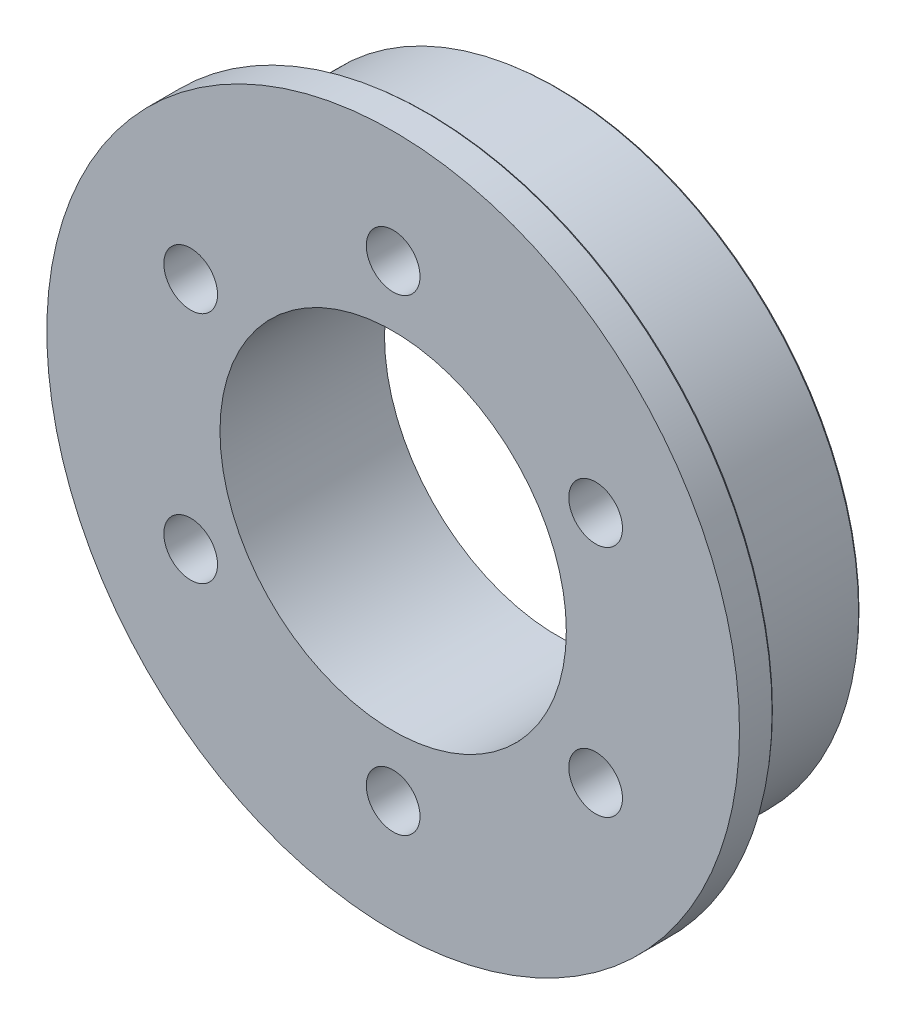
SolidWorks part; units mm, degrees
material "1060 合金"
ref_plane "前视基准面" through (0, 0, 0) normal (0, 0, 1) x (1, 0, 0)
ref_plane "上视基准面" through (0, 0, 0) normal (0, 1, 0) x (1, 0, 0)
ref_plane "右视基准面" through (0, 0, 0) normal (1, 0, 0) x (0, 0, -1)
sketch "草图1" plane through (0, 0, 0) normal (0, 0, 1) x (1, 0, 0)
  circle A0 centre (0, 0) radius 13.5 construction
  circle A1 centre (0, 13.5) radius 1.55
  circle A2 centre (11.6913, 6.75) radius 1.55
  circle A3 centre (11.6913, -6.75) radius 1.55
  circle A4 centre (0, -13.5) radius 1.55
  circle A5 centre (-11.6913, -6.75) radius 1.55
  circle A6 centre (-11.6913, 6.75) radius 1.55
  circle A7 centre (0, 0) radius 17.5
  point P17 (0, 0)
  dimension "D1" = 27
  dimension "D2" = 3.1
  dimension "D4" = 35
  dimension "D3" = 6
extrude "凸台-拉伸1" add sketch "草图1" along normal blind 7.5
sketch "草图2" plane through (0, 0, 7.5) normal (0, 0, 1) x (1, 0, 0)
  circle A0 centre (0, 0) radius 20
  circle A1 centre (11.6913, 6.75) radius 1.55 construction
  circle A2 centre (11.6913, -6.75) radius 1.55 construction
  circle A3 centre (0, -13.5) radius 1.55 construction
  circle A4 centre (-11.6913, -6.75) radius 1.55 construction
  circle A5 centre (-11.6913, 6.75) radius 1.55 construction
  circle A6 centre (0, 13.5) radius 1.55 construction
  circle A7 centre (11.6913, 6.75) radius 1.55
  circle A8 centre (11.6913, -6.75) radius 1.55
  circle A9 centre (0, -13.5) radius 1.55
  circle A10 centre (-11.6913, -6.75) radius 1.55
  circle A11 centre (-11.6913, 6.75) radius 1.55
  circle A12 centre (0, 13.5) radius 1.55
  dimension "D1" = 40
extrude "凸台-拉伸2" add sketch "草图2" along normal blind 2
chamfer "倒角1" distance 0.1 angle 50 2 edges at (20, 0, 7.5) (17.5, 0, 0)
sketch "草图4" plane through (0, 0, 0) normal (0, 0, -1) x (-1, 0, 0)
  circle A0 centre (0, 0) radius 10
  dimension "D1" = 20
extrude "切除-拉伸1" cut sketch "草图4" against normal blind 25
